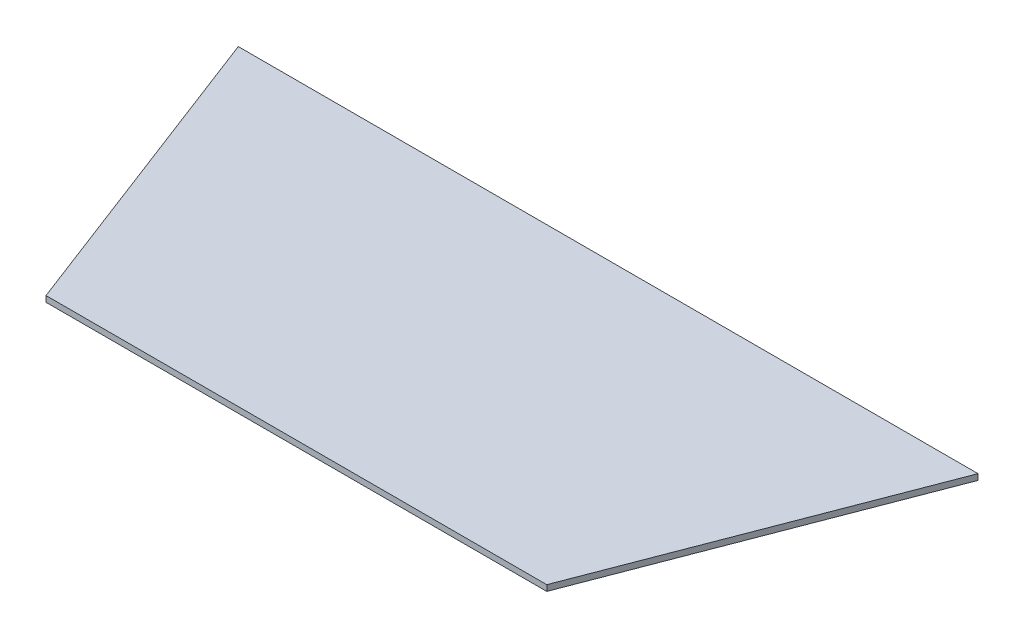
SolidWorks part; units mm, degrees
ref_plane "Front Plane" through (0, 0, 0) normal (0, 0, 1) x (1, 0, 0)
ref_plane "Top Plane" through (0, 0, 0) normal (0, 1, 0) x (1, 0, 0)
ref_plane "Right Plane" through (0, 0, 0) normal (1, 0, 0) x (0, 0, -1)
sketch "Sketch1" plane through (0, 0, 0) normal (0, 1, 0) x (1, 0, 0)
  line L2 (125.7609, 106) -> (85.135, 0)
  line L3 (85.135, 0) -> (-85.135, 0)
  line L4 (-85.135, 0) -> (-125.7609, 106)
  line L6 (-125.7609, 106) -> (125.7609, 106)
  line L7 (0, 106) -> (0, 0) construction
  dimension "D1" = 110.97
  dimension "D2" = 170.27
  dimension "D3" = 106
extrude "Boss-Extrude1" add sketch "Sketch1" along normal blind 2
equation "\"clip_tube_diam\"= 6mm"
equation "\"middle_tube_len\"= 500mm"
equation "\"horizontal_pipe_spacing\"= 260mm"
equation "\"belly_plate_width\" = 176mm"
equation "\"belly_bottom_width\" = 170.267mm"
equation "\"belly_length\"  = 500mm"
